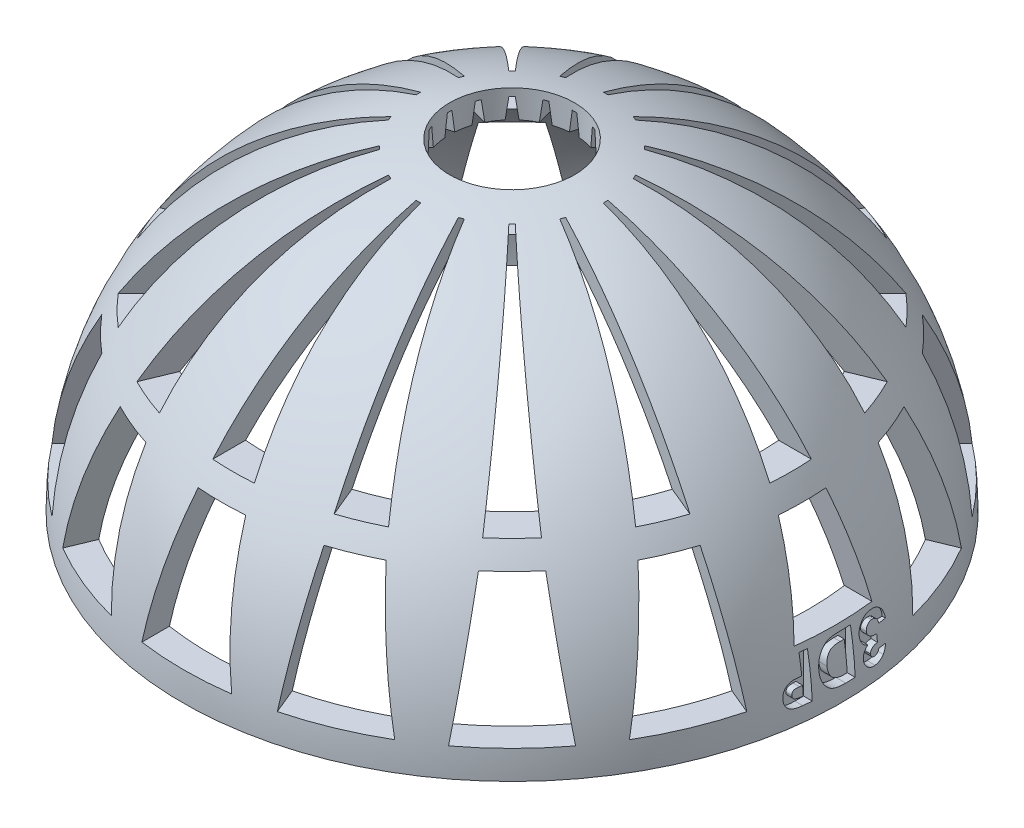
SolidWorks part; units mm, degrees
ref_plane "Front Plane" through (0, 0, 0) normal (0, 0, 1) x (1, 0, 0)
ref_plane "Top Plane" through (0, 0, 0) normal (0, 1, 0) x (1, 0, 0)
ref_plane "Right Plane" through (0, 0, 0) normal (1, 0, 0) x (0, 0, -1)
sketch "Sketch7" plane through (0, 0, 0) normal (0, 0, 1) x (1, 0, 0)
  line L0 (0, 0) -> (0, 48.5) construction
  line L1 (0, 0) -> (48.5, 0) construction
  line L2 (44.5, 0) -> (48.5, 0)
  line L3 (0, 44.5) -> (0, 48.5)
  arc A0 (0, 48.5) -> (48.5, 0) centre (0, 0) cw
  arc A1 (0, 44.5) -> (44.5, 0) centre (0, 0) cw
  dimension "D1" = 48.5
  dimension "D2" = 4
revolve "Revolve2" add sketch "Sketch7" angle 360 about L0
ref_plane "Plane3" through (50.5, 0, 0) normal (1, 0, 0) x (0, 0, -1)
sketch "Sketch8" plane through (50.5, 0, 0) normal (1, 0, 0) x (0, 0, -1)
  line L0 (0, 0) -> (0, 48.5) construction
  line L1 (-42.8333, 22.75) -> (42.8333, 22.75) construction
  line L2 (-3.5, 22.75) -> (-6.6114, 4.0955)
  line L3 (-6.6114, 4.0955) -> (6.6114, 4.0955)
  line L4 (6.6114, 4.0955) -> (3.5, 22.75)
  line L5 (3.5, 22.75) -> (-3.5, 22.75)
  line L6 (-42.0022, 24.25) -> (42.0022, 24.25) construction
  line L7 (-41.0997, 25.75) -> (41.0997, 25.75) construction
  line L8 (-13.784, 46.5) -> (13.784, 46.5) construction
  line L9 (-3.0603, 25.75) -> (-0.3359, 46.5)
  line L10 (-0.3359, 46.5) -> (0.3359, 46.5)
  line L11 (0.3359, 46.5) -> (3.0603, 25.75)
  line L12 (3.0603, 25.75) -> (-3.0603, 25.75)
  arc A0 (48.5, 0) -> (-48.5, 0) centre (0, 0) ccw construction
  point P10 (0, 22.75)
  point P13 (0, 4.0955)
  point P22 (0, 24.25)
  dimension "D1" = 3
  dimension "D2" = 1.5
  dimension "D3" = 2
  dimension "D4" = 7
extrude "Cut-Extrude1" cut sketch "Sketch8" against normal blind 48.5
pattern_circular "CirPattern1" count 16 over 360 about axis through (0, 0, 0) along (0, 1, 0) of "Cut-Extrude1"
ref_plane "Plane4" through (0, 43.5, 0) normal (0, 1, 0) x (1, 0, 0)
sketch "Sketch9" plane through (0, 43.5, 0) normal (0, 1, 0) x (1, 0, 0)
  circle A0 centre (0, 0) radius 9.1935
extrude "Cut-Extrude2" cut sketch "Sketch9" along normal blind 13.5
sketch "Sketch11" plane through (0, 0, 0) normal (0, 0, 1) x (1, 0, 0)
  line L0 (48.5, 0) -> (44.5, 0)
  line L1 (-48.5, 0) -> (48.5, 0) construction
  line L2 (47.5755, 9.4244) -> (43.5755, 9.4244)
  arc A0 (48.5, 0) -> (41.9933, 24.2655) centre (0, 0) ccw construction
  arc A1 (42.8333, 22.75) -> (41.0997, 25.75) centre (0, 0) ccw construction
  arc A2 (48.5, 0) -> (47.5755, 9.4244) centre (0, 0) ccw
  arc A3 (43.5755, 9.4244) -> (44.5, 0) centre (-4, 0) cw
  dimension "D1" = 4
  dimension "D2" = 4
revolve "Revolve3" add sketch "Sketch11" angle 10
sketch "Sketch12" plane through (50.5, 0, 0) normal (1, 0, 0) x (0, 0, -1)
  line L0 (7.701, 8.4997) -> (-9.6663, 8.4997) construction
  line L2 (0, 0) -> (0, 12.8952) construction
  line L3 (0, 26.6366) -> (0, -53.2732) construction
  text T0 "<b>3DP</b>" font "Century Gothic" height in points 24
extrude "Cut-Extrude3" cut sketch "Sketch12" against normal blind 3.5
